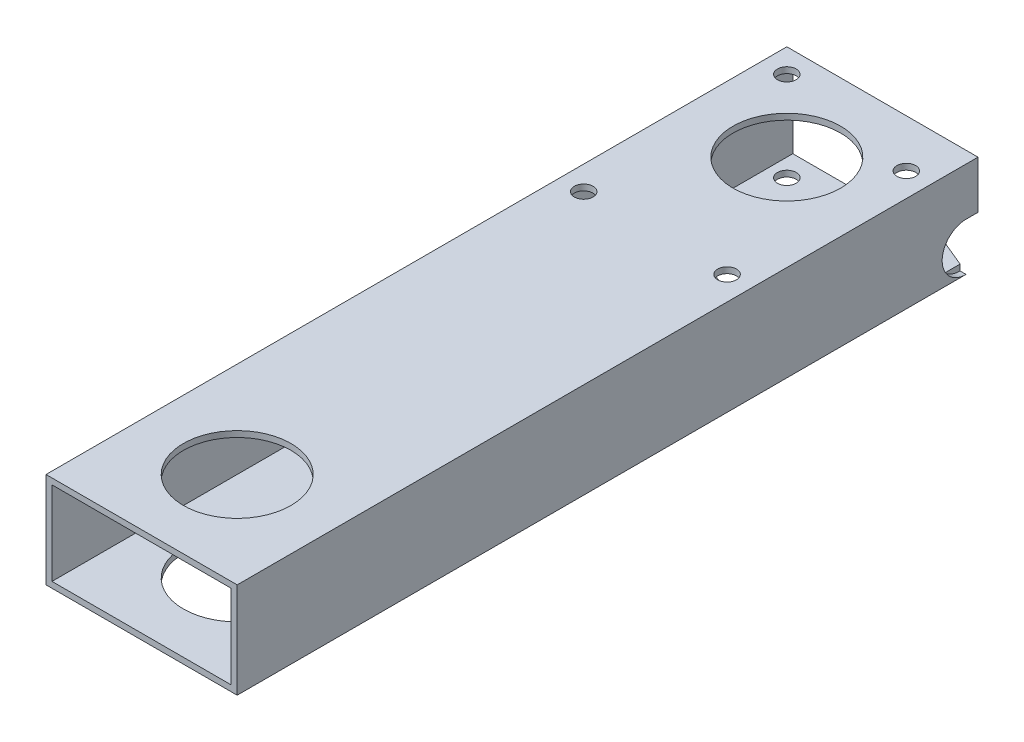
SolidWorks part; units mm, degrees
material "6061 Alloy"
ref_plane "Front Plane" through (0, 0, 0) normal (0, 0, 1) x (1, 0, 0)
ref_plane "Top Plane" through (0, 0, 0) normal (0, 1, 0) x (1, 0, 0)
ref_plane "Right Plane" through (0, 0, 0) normal (1, 0, 0) x (0, 0, -1)
sketch "Sketch1" plane through (0, 0, 0) normal (0, 0, 1) x (1, 0, 0)
  line L0 (-23.8125, 11.1125) -> (23.8125, 11.1125)
  line L2 (-25.4, 12.7) -> (25.4, 12.7)
  line L3 (-25.4, 12.7) -> (-25.4, -12.7)
  line L4 (-25.4, -12.7) -> (25.4, -12.7)
  line L5 (25.4, 12.7) -> (25.4, -12.7)
  line L10 (23.8125, 11.1125) -> (23.8125, -11.1125)
  line L11 (-23.8125, -11.1125) -> (23.8125, -11.1125)
  line L12 (-23.8125, 11.1125) -> (-23.8125, -11.1125)
  point P12 (0, 12.7)
  point P14 (25.4, 0)
  dimension "Wall Thickness" = 1.5875
  dimension "Outside Width" = 50.8
  dimension "Outside Height" = 25.4
  dimension "Inside Height" = 22.225
  dimension "Inside Width" = 47.625
sketch "Sketch2" plane through (0, 0, 0) normal (1, 0, 0) x (0, 0, -1)
  line L0 (98.425, 0) -> (-98.425, 0)
  point P4 (0, 0)
  point P7 (-98.425, 0)
  point P10 (98.425, 0)
  dimension "Length" = 196.85
sketch "Sketch3" plane through (0, 0, 0) normal (0, 0, 1) x (1, 0, 0)
  line L21 (25.4, 12.7) -> (-25.4, 12.7)
  line L22 (25.4, -12.7) -> (25.4, 12.7)
  line L23 (-25.4, -12.7) -> (25.4, -12.7)
  line L24 (-25.4, 12.7) -> (-25.4, -12.7)
  line L25 (25.4, 12.7) -> (-25.4, 12.7)
  line L26 (25.4, -12.7) -> (25.4, 12.7)
  line L27 (-25.4, -12.7) -> (25.4, -12.7)
  line L28 (-25.4, 12.7) -> (-25.4, -12.7)
  line L29 (23.8125, 11.1125) -> (-23.8125, 11.1125)
  line L30 (23.8125, -11.1125) -> (23.8125, 11.1125)
  line L31 (-23.8125, -11.1125) -> (23.8125, -11.1125)
  line L32 (-23.8125, 11.1125) -> (-23.8125, -11.1125)
  line L33 (23.8125, 11.1125) -> (-23.8125, 11.1125)
  line L34 (23.8125, -11.1125) -> (23.8125, 11.1125)
  line L35 (-23.8125, -11.1125) -> (23.8125, -11.1125)
  line L36 (-23.8125, 11.1125) -> (-23.8125, -11.1125)
  dimension "D1" = 0
  dimension "D2" = 0
extrude "Boss-Extrude1" add sketch "Sketch3" along normal up to vertex (98.425 mm away) and the other way up to vertex (98.425 mm away) up to point (0, 0, 98.425) other way up to point (0, 0, -98.425)
sketch "Drawing Reference" plane through (0, 0, 0) normal (1, 0, 0) x (0, 0, -1)
  line L0 (-98.425, 0) -> (98.425, 0) construction
  line L1 (0, -12.7) -> (0, 12.7) construction
  line L2 (-98.425, -12.7) -> (98.425, -12.7) construction
  line L5 (-98.425, 12.7) -> (98.425, 12.7) construction
  point P7 (-61.849, 0)
  point P8 (61.849, 0)
  dimension "D1" = 36.576
sketch "Sketch4" plane through (0, -12.7, 0) normal (0, -1, 0) x (1, 0, 0)
  line L0 (-25.4, 0) -> (0, 0) construction
  line L1 (-25.4, 98.425) -> (-25.4, -98.425) construction
  line L2 (0, 0) -> (0, -73.025) construction
  line L3 (0, 0) -> (0, 73.025) construction
  circle A0 centre (0, 73.025) radius 14.2875
  circle A1 centre (0, -73.025) radius 14.2875
extrude "Cut-Extrude3" cut sketch "Sketch4" against normal through all
sketch "Sketch5" plane through (25.4, 0, 0) normal (1, 0, 0) x (0, 0, -1)
  line L7 (98.425, -12.7) -> (98.425, 12.7) construction
  line L8 (98.425, 0) -> (98.425, -12.7)
  line L9 (98.425, -12.7) -> (95.25, -12.7)
  line L10 (95.25, 0) -> (98.425, 0)
  arc A0 (95.25, 0) -> (95.25, -12.7) centre (95.25, -6.35) ccw
  dimension "D1" = 6.35
extrude "Cut-Extrude5" cut sketch "Sketch5" against normal blind 1.5875
sketch "Sketch6" plane through (0, -12.7, 0) normal (0, -1, 0) x (1, 0, 0)
  line L0 (23.8125, -98.425) -> (23.8125, -95.25)
  line L1 (23.8125, -95.25) -> (16.1925, -98.425)
  line L2 (-25.4, -98.425) -> (23.8125, -98.425) construction
  line L3 (16.1925, -98.425) -> (23.8125, -98.425)
  dimension "D1" = 7.62
extrude "Cut-Extrude6" cut sketch "Sketch6" against normal blind 1.5875
hole_wizard "#10 Clearance Hole1" positions "Sketch7" profile "Sketch8" hole size "#10" standard "ANSI Inch" end condition through all
sketch "Sketch7" plane through (0, -12.7, 0) normal (0, -1, 0) x (-1, 0, 0)
  point P0 (-19.05, 85.725)
  point P3 (19.05, 92.075)
  point P6 (19.05, 38.1)
  point P9 (-19.05, 38.1)
sketch "Sketch8" plane through (19.05, -12.7, -85.725) normal (1, 0, 0) x (0, 0, -1)
  line L0 (0, 0) -> (0, 25.4)
  line L1 (0, 25.4) -> (2.4892, 25.4)
  line L2 (2.4892, 25.4) -> (2.4892, 0)
  line L5 (2.4892, 0) -> (0, 0)
  line L11 (0, -6.35) -> (0, 107.95) construction
  dimension "Thru Hole Dia." = 4.9784
  dimension "Thru Hole Depth" = 25.4
equation "\"D1@Drawing Reference\"=\"Outside Width@Sketch1\" * 0.72"
